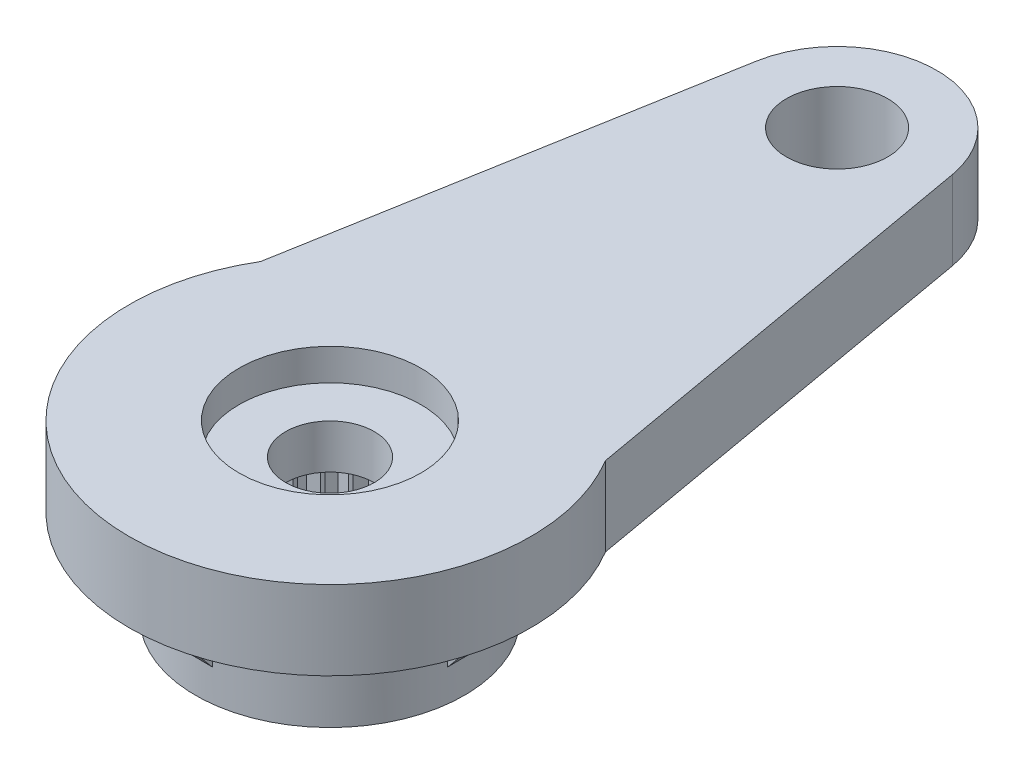
SolidWorks part; units mm, degrees
material "PC High Viscosity"
ref_plane "Front Plane" through (0, 0, 0) normal (0, 0, 1) x (1, 0, 0)
ref_plane "Top Plane" through (0, 0, 0) normal (0, 1, 0) x (1, 0, 0)
ref_plane "Right Plane" through (0, 0, 0) normal (1, 0, 0) x (0, 0, -1)
sketch "BaseS" plane through (0, 0, 0) normal (0, 1, 0) x (1, 0, 0)
  circle A0 centre (0, 0) radius 6.35
  dimension "D1" = 12.7
extrude "BASE" add sketch "BaseS" along normal blind 5.4
sketch "TopBoreS" plane through (0, 5.4, 0) normal (0, 1, 0) x (1, 0, 0)
  circle A0 centre (0, 0) radius 1.4
  dimension "D1" = 2.8
extrude "TOP BORE" cut sketch "TopBoreS" against normal through all
sketch "HornHalfS" plane through (0, 5.4, 0) normal (0, 1, 0) x (1, 0, 0)
  line L0 (0, 0) -> (0, 16.03) construction
  line L1 (-3.1021, 16.577) -> (-5.4507, 3.2577)
  line L2 (0, 19.18) -> (0, 16.03) construction
  line L3 (3.1021, 16.577) -> (5.4507, 3.2577)
  arc A0 (3.1021, 16.577) -> (-3.1021, 16.577) centre (0, 16.03) ccw
  arc A1 (5.4507, 3.2577) -> (-5.4507, 3.2577) centre (0, 0) ccw
  circle A2 centre (0, 0) radius 6.35 construction
  dimension "D1" = 6.3
  dimension "D2" = 19.18
  dimension "D3" = 10
  dimension "D4" = 10.9014
extrude "HORN HALF" add sketch "HornHalfS" against normal blind 2.5
sketch "HornAttachS" plane through (0, 5.4, 0) normal (0, 1, 0) x (1, 0, 0)
  circle A0 centre (0, 16.03) radius 1.6
  point P3 (0, 0)
  dimension "D1" = 3.2
extrude "HORN ATTACH" cut sketch "HornAttachS" against normal through all
sketch "HA LP RS" plane through (0, 0, 0) normal (0, 1, 0) x (1, 0, 0)
  line L0 (0, 0) -> (0, 16.03) construction
  point P4 (0, 0)
sketch "ToothS" plane through (0, 0, 0) normal (0, -1, 0) x (1, 0, 0)
  line L0 (0, -2.9) -> (0.2629, -2.5867)
  line L1 (0, -2.9) -> (-0.2629, -2.5867)
  line L2 (0, -2.6) -> (0, -2.9) construction
  line L3 (0, 0) -> (0, -2.6) construction
  arc A0 (-0.2629, -2.5867) -> (0.2629, -2.5867) centre (0, 0) ccw
  dimension "D1" = 5.2
  dimension "D2" = 80
  dimension "D3" = 0.3
extrude "TOOTH" cut sketch "ToothS" against normal blind 3
pattern_circular "TOOTH CP" count 26 over 360 about axis through (0, 0, 0) along (0, 1, 0) of "TOOTH"
sketch "BottomBoreS" plane through (0, 0, 0) normal (0, -1, 0) x (-1, 0, 0)
  circle A0 centre (0, 0) radius 2.6
  arc A1 (0.2629, 2.5867) -> (-0.2629, 2.5867) centre (0, 0) ccw construction
extrude "BOTTOM BORE" cut sketch "BottomBoreS" against normal up to surface (3 mm away) up to face at (-0.6451, 3, 2.6172)
sketch "HoldingShaftS" plane through (0, 0, 0) normal (0, -1, 0) x (1, 0, 0)
  circle A0 centre (0, 0) radius 6.35 construction
  circle A1 centre (0, 0) radius 6.35
  circle A2 centre (0, 0) radius 4.25
  dimension "D1" = 2.1
  dimension "D2" = 8.5
extrude "HOLDING SHAFT" cut sketch "HoldingShaftS" against normal up to surface (2.9 mm away) up to face at (0, 2.9, -14.43)
sketch "RibS" plane through (0, 0, 0) normal (0, 0, 1) x (1, 0, 0)
  line L0 (4.21, 1) -> (5.8043, 2.9)
  line L1 (5.8043, 2.9) -> (4.21, 2.9)
  line L2 (4.21, 1) -> (4.16, 1)
  line L3 (4.16, 1) -> (4.16, 2.9)
  line L4 (4.21, 1) -> (4.21, 2.9) construction
  line L5 (4.16, 2.9) -> (4.21, 2.9)
  line L6 (-4.25, 2.9) -> (4.25, 2.9) construction
  line L7 (4.21, 2.9) -> (4.25, 2.9) construction
  line L8 (4.25, 0) -> (4.25, 2.9) construction
  dimension "D1" = 1.9
  dimension "D2" = 0.05
  dimension "D3" = 40
  dimension "D4" = 0.09
extrude "RIB" add sketch "RibS" along normal mid plane 1
pattern_circular "RIB CP" count 4 over 360 about axis through (0, 0, 0) along (0, 1, 0) of "RIB"
sketch "Sketch1" plane through (0, 5.4, 0) normal (0, 1, 0) x (1, 0, 0)
  circle A0 centre (0, 0) radius 2.875
  dimension "D1" = 5.75
extrude "Cut-Extrude1" cut sketch "Sketch1" against normal blind 1
ref_point "Point1"
